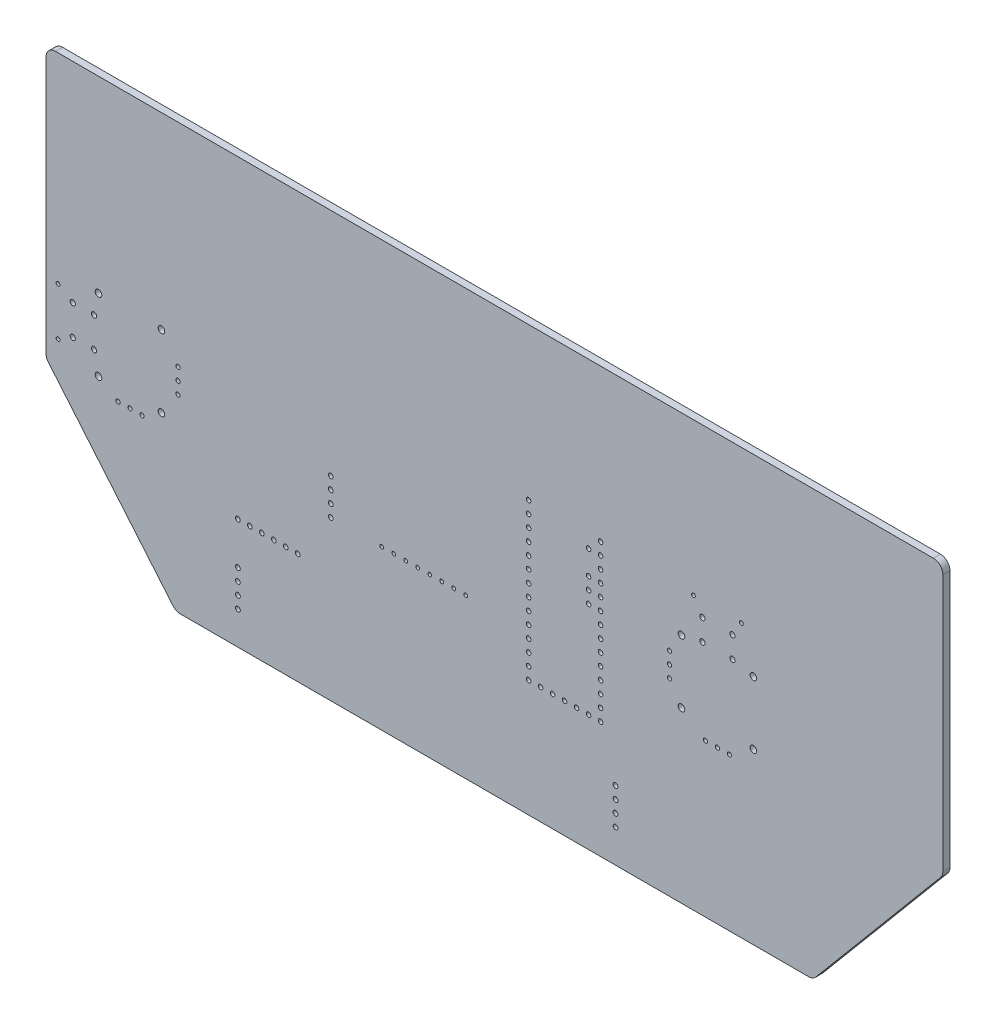
SolidWorks part; units mm, degrees
ref_plane "Front Plane" through (0, 0, 0) normal (0, 0, 1) x (1, 0, 0)
ref_plane "Top Plane" through (0, 0, 0) normal (0, 1, 0) x (1, 0, 0)
ref_plane "Right Plane" through (0, 0, 0) normal (1, 0, 0) x (0, 0, -1)
ref_plane "Plane1" through (0, 0, 1.5) normal (0, 0, 1) x (1, 0, 0)
sketch "Sketch1" plane through (0, 0, 1.5) normal (0, 0, 1) x (1, 0, 0)
  line L0 (190, 33.5012) -> (190, 88)
  line L1 (188, 90) -> (2, 90)
  line L2 (0, 88) -> (0, 33.5012)
  line L3 (0.4679, 32.2156) -> (26.9005, 0.7144)
  line L4 (28.4326, 0) -> (161.5674, 0)
  line L5 (163.0995, 0.7144) -> (189.5321, 32.2156)
  arc A0 (189.5321, 32.2156) -> (190, 33.5012) centre (188, 33.5012) ccw
  arc A1 (190, 88) -> (188, 90) centre (188, 88) ccw
  arc A2 (2, 90) -> (0, 88) centre (2, 88) ccw
  arc A3 (0, 33.5012) -> (0.4679, 32.2156) centre (2, 33.5012) ccw
  arc A4 (26.9005, 0.7144) -> (28.4326, 0) centre (28.4326, 2) ccw
  arc A5 (161.5674, 0) -> (163.0995, 0.7144) centre (161.5674, 2) ccw
  circle A6 centre (86.36, 33.655) radius 0.4
  circle A7 centre (71.12, 33.655) radius 0.4
  circle A8 centre (76.2, 33.655) radius 0.4
  circle A9 centre (78.74, 33.655) radius 0.4
  circle A10 centre (2.54, 47.625) radius 0.4064
  circle A11 centre (137.16, 57.785) radius 0.4064
  circle A12 centre (142.24, 32.385) radius 0.4445
  circle A13 centre (132.08, 42.545) radius 0.4445
  circle A14 centre (27.94, 45.085) radius 0.4445
  circle A15 centre (27.94, 40.005) radius 0.4445
  circle A16 centre (132.08, 40.005) radius 0.4445
  circle A17 centre (15.24, 32.385) radius 0.4445
  circle A18 centre (102.235, 57.785) radius 0.4826
  circle A19 centre (114.935, 47.625) radius 0.4826
  circle A20 centre (114.935, 55.245) radius 0.4826
  circle A21 centre (117.475, 55.245) radius 0.4826
  circle A22 centre (117.475, 50.165) radius 0.4826
  circle A23 centre (117.475, 45.085) radius 0.4826
  circle A24 centre (117.475, 40.005) radius 0.4826
  circle A25 centre (117.475, 34.925) radius 0.4826
  circle A26 centre (117.475, 29.845) radius 0.4826
  circle A27 centre (117.475, 24.765) radius 0.4826
  circle A28 centre (112.395, 24.765) radius 0.4826
  circle A29 centre (107.315, 24.765) radius 0.4826
  circle A30 centre (102.235, 24.765) radius 0.4826
  circle A31 centre (102.235, 29.845) radius 0.4826
  circle A32 centre (102.235, 34.925) radius 0.4826
  circle A33 centre (102.235, 40.005) radius 0.4826
  circle A34 centre (102.235, 45.085) radius 0.4826
  circle A35 centre (102.235, 50.165) radius 0.4826
  circle A36 centre (43.18, 23.495) radius 0.5
  circle A37 centre (48.26, 23.495) radius 0.5
  circle A38 centre (53.34, 23.495) radius 0.5
  circle A39 centre (120.65, 9.525) radius 0.508
  circle A40 centre (120.65, 6.985) radius 0.508
  circle A41 centre (60.325, 36.195) radius 0.508
  circle A42 centre (60.325, 41.275) radius 0.508
  circle A43 centre (40.64, 12.065) radius 0.508
  circle A44 centre (40.64, 6.985) radius 0.508
  circle A45 centre (5.66, 45.72) radius 0.55
  circle A46 centre (10.16, 39.37) radius 0.55
  circle A47 centre (145.415, 54.665) radius 0.55
  circle A48 centre (139.065, 50.165) radius 0.55
  circle A49 centre (11.1125, 50.165) radius 0.6985
  circle A50 centre (24.4475, 34.925) radius 0.6985
  circle A51 centre (134.62, 35.8775) radius 0.6985
  circle A52 centre (149.86, 49.2125) radius 0.6985
  circle A53 centre (134.62, 49.2125) radius 0.6985
  circle A54 centre (149.86, 35.8775) radius 0.6985
  circle A55 centre (24.4475, 50.165) radius 0.6985
  circle A56 centre (11.1125, 34.925) radius 0.6985
  circle A57 centre (145.415, 50.165) radius 0.55
  circle A58 centre (139.065, 54.665) radius 0.55
  circle A59 centre (10.16, 45.72) radius 0.55
  circle A60 centre (5.66, 39.37) radius 0.55
  circle A61 centre (120.65, 14.605) radius 0.508
  circle A62 centre (40.64, 9.525) radius 0.508
  circle A63 centre (40.64, 14.605) radius 0.508
  circle A64 centre (60.325, 38.735) radius 0.508
  circle A65 centre (60.325, 33.655) radius 0.508
  circle A66 centre (120.65, 12.065) radius 0.508
  circle A67 centre (40.64, 23.495) radius 0.5
  circle A68 centre (50.8, 23.495) radius 0.5
  circle A69 centre (45.72, 23.495) radius 0.5
  circle A70 centre (102.235, 52.705) radius 0.4826
  circle A71 centre (102.235, 47.625) radius 0.4826
  circle A72 centre (102.235, 42.545) radius 0.4826
  circle A73 centre (102.235, 37.465) radius 0.4826
  circle A74 centre (102.235, 32.385) radius 0.4826
  circle A75 centre (102.235, 27.305) radius 0.4826
  circle A76 centre (104.775, 24.765) radius 0.4826
  circle A77 centre (109.855, 24.765) radius 0.4826
  circle A78 centre (114.935, 24.765) radius 0.4826
  circle A79 centre (117.475, 27.305) radius 0.4826
  circle A80 centre (117.475, 32.385) radius 0.4826
  circle A81 centre (117.475, 37.465) radius 0.4826
  circle A82 centre (117.475, 42.545) radius 0.4826
  circle A83 centre (117.475, 47.625) radius 0.4826
  circle A84 centre (117.475, 52.705) radius 0.4826
  circle A85 centre (117.475, 57.785) radius 0.4826
  circle A86 centre (114.935, 50.165) radius 0.4826
  circle A87 centre (114.935, 45.085) radius 0.4826
  circle A88 centre (102.235, 55.245) radius 0.4826
  circle A89 centre (20.32, 32.385) radius 0.4445
  circle A90 centre (17.78, 32.385) radius 0.4445
  circle A91 centre (27.94, 42.545) radius 0.4445
  circle A92 centre (132.08, 45.085) radius 0.4445
  circle A93 centre (139.7, 32.385) radius 0.4445
  circle A94 centre (144.78, 32.385) radius 0.4445
  circle A95 centre (147.32, 57.785) radius 0.4064
  circle A96 centre (2.54, 37.465) radius 0.4064
  circle A97 centre (81.28, 33.655) radius 0.4
  circle A98 centre (73.66, 33.655) radius 0.4
  circle A99 centre (83.82, 33.655) radius 0.4
  circle A100 centre (88.9, 33.655) radius 0.4
extrude "Boss-Extrude1" add sketch "Sketch1" against normal blind 1.5
sketch "Sketch2" plane through (0, 0, 1.5) normal (0, 0, 1) x (1, 0, 0)
  point P0 (25.75, 65.8)
  point P1 (164.75, 65.8)
